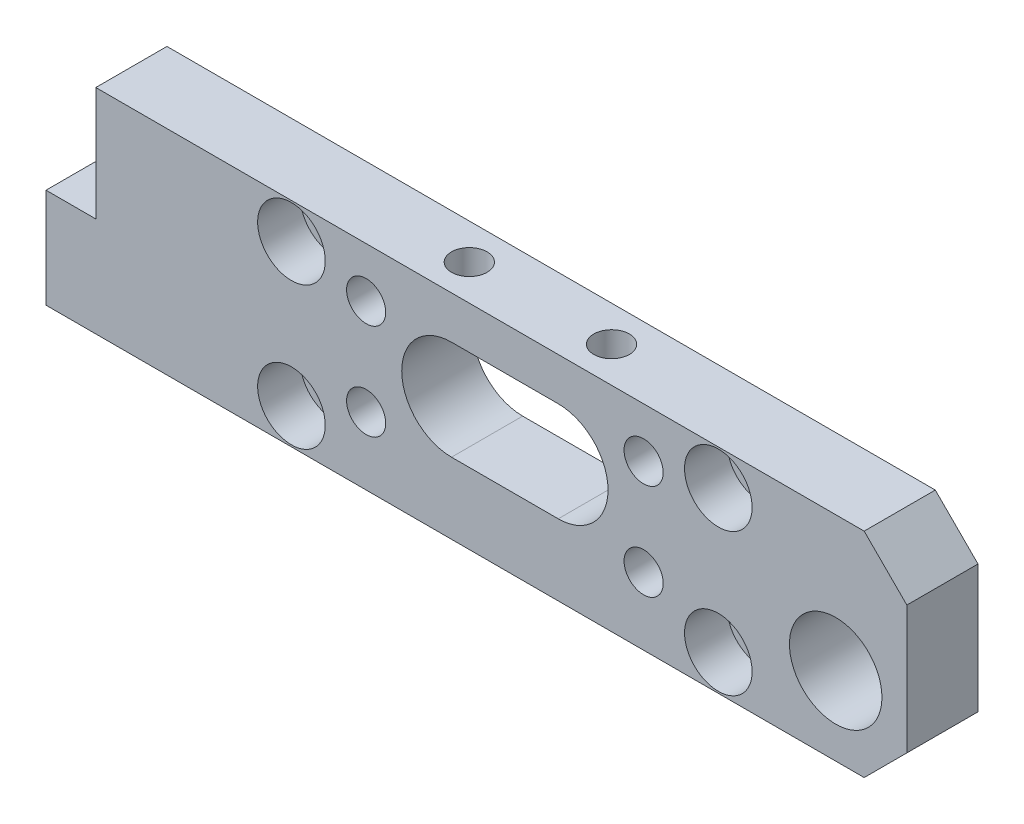
SolidWorks part; units mm, degrees
ref_plane "前视基准面" through (0, 0, 0) normal (0, 0, 1) x (1, 0, 0)
ref_plane "上视基准面" through (0, 0, 0) normal (0, 1, 0) x (1, 0, 0)
ref_plane "右视基准面" through (0, 0, 0) normal (1, 0, 0) x (0, 0, -1)
sketch "草图1" plane through (0, 0, 0) normal (0, 0, 1) x (1, 0, 0)
  line L93 (1458.0245, 1041.6792) -> (1458.0245, 1025.6792)
  line L94 (1451.0245, 1011.6792) -> (1566.0245, 1011.6792)
  line L95 (1572.0245, 1017.6792) -> (1566.0245, 1011.6792)
  line L96 (1572.0245, 1017.6792) -> (1572.0245, 1035.6792)
  line L97 (1508.0245, 1035.6792) -> (1523.0245, 1035.6792)
  line L98 (1508.0245, 1021.6792) -> (1523.0245, 1021.6792)
  line L109 (1566.0245, 1041.6792) -> (1458.0245, 1041.6792)
  line L110 (1572.0245, 1035.6792) -> (1566.0245, 1041.6792)
  line L111 (1552.6399, 1022.6792) -> (1571.0512, 1022.6792) construction
  line L112 (1562.0245, 1030.9775) -> (1562.0245, 1014.0973) construction
  line L113 (1539.7634, 1016.6792) -> (1551.5723, 1016.6792) construction
  line L114 (1545.5245, 1023.4237) -> (1545.5245, 1011.0186) construction
  line L115 (1535.0245, 1027.9237) -> (1535.0245, 1015.5186) construction
  line L116 (1529.2634, 1021.1792) -> (1541.0723, 1021.1792) construction
  line L117 (1545.5245, 1043.4237) -> (1545.5245, 1031.0186) construction
  line L118 (1539.7634, 1036.6792) -> (1551.5723, 1036.6792) construction
  line L119 (1535.0245, 1041.4237) -> (1535.0245, 1029.0186) construction
  line L120 (1529.2634, 1034.6792) -> (1541.0723, 1034.6792) construction
  line L121 (1496.0245, 1041.4237) -> (1496.0245, 1029.0186) construction
  line L122 (1490.2634, 1034.6792) -> (1502.0723, 1034.6792) construction
  line L123 (1496.0245, 1027.9237) -> (1496.0245, 1015.5186) construction
  line L124 (1490.2634, 1021.1792) -> (1502.0723, 1021.1792) construction
  line L125 (1485.5245, 1043.4237) -> (1485.5245, 1031.0186) construction
  line L126 (1479.7634, 1036.6792) -> (1491.5723, 1036.6792) construction
  line L127 (1485.5245, 1023.4237) -> (1485.5245, 1011.0186) construction
  line L128 (1479.7634, 1016.6792) -> (1491.5723, 1016.6792) construction
  line L129 (1498.3438, 1028.6792) -> (1533.0612, 1028.6792) construction
  line L131 (1523.0245, 1020.3405) -> (1523.0245, 1036.6859) construction
  line L132 (1451.0245, 1025.6792) -> (1458.0245, 1025.6792)
  line L133 (1451.0245, 1025.6792) -> (1451.0245, 1011.6792)
  circle A8 centre (1545.5245, 1016.6792) radius 2.75
  circle A10 centre (1485.5245, 1016.6792) radius 2.75
  circle A13 centre (1485.5245, 1036.6792) radius 2.75
  circle A15 centre (1545.5245, 1036.6792) radius 2.75
  circle A16 centre (1496.0245, 1021.1792) radius 2.75
  circle A18 centre (1535.0245, 1021.1792) radius 2.75
  circle A21 centre (1535.0245, 1034.6792) radius 2.75
  circle A23 centre (1496.0245, 1034.6792) radius 2.75
  arc A24 (1523.0245, 1021.6792) -> (1523.0245, 1035.6792) centre (1523.0245, 1028.6792) ccw
  arc A25 (1508.0245, 1035.6792) -> (1508.0245, 1021.6792) centre (1508.0245, 1028.6792) ccw
  circle A26 centre (1562.0245, 1022.6792) radius 6.5
extrude "拉伸1" add sketch "草图1" along normal blind 10
sketch "草图2" plane through (0, 0, 10) normal (0, 0, 1) x (1, 0, 0)
  circle A0 centre (1485.5245, 1036.6792) radius 4.75
  circle A1 centre (1545.5245, 1036.6792) radius 4.75
  circle A2 centre (1485.5245, 1016.6792) radius 4.75
  circle A3 centre (1545.5245, 1016.6792) radius 4.75
  dimension "D1" = 9.5
extrude "拉伸2" cut sketch "草图2" against normal blind 6
sketch "草图3" plane through (0, 0, 0) normal (0, 0, -1) x (-1, 0, 0)
  circle A0 centre (-1535.0245, 1034.6792) radius 4.75
  circle A1 centre (-1496.0245, 1034.6792) radius 4.75
  circle A2 centre (-1535.0245, 1021.1792) radius 4.75
  circle A3 centre (-1496.0245, 1021.1792) radius 4.75
  dimension "D1" = 9.5
extrude "拉伸3" cut sketch "草图3" against normal blind 6
sketch "草图4" plane through (0, 1041.6792, 0) normal (0, 1, 0) x (1, 0, 0)
  line L1 (1451.0245, -10) -> (1451.0245, 0) construction
  line L2 (1566.0245, -10) -> (1458.0245, -10) construction
  circle A0 centre (1505.5245, -5) radius 2.5
  circle A1 centre (1525.5245, -5) radius 2.5
  dimension "D1" = 5
  dimension "D2" = 54.5
  dimension "D3" = 5
extrude "拉伸4" cut sketch "草图4" against normal up to next
